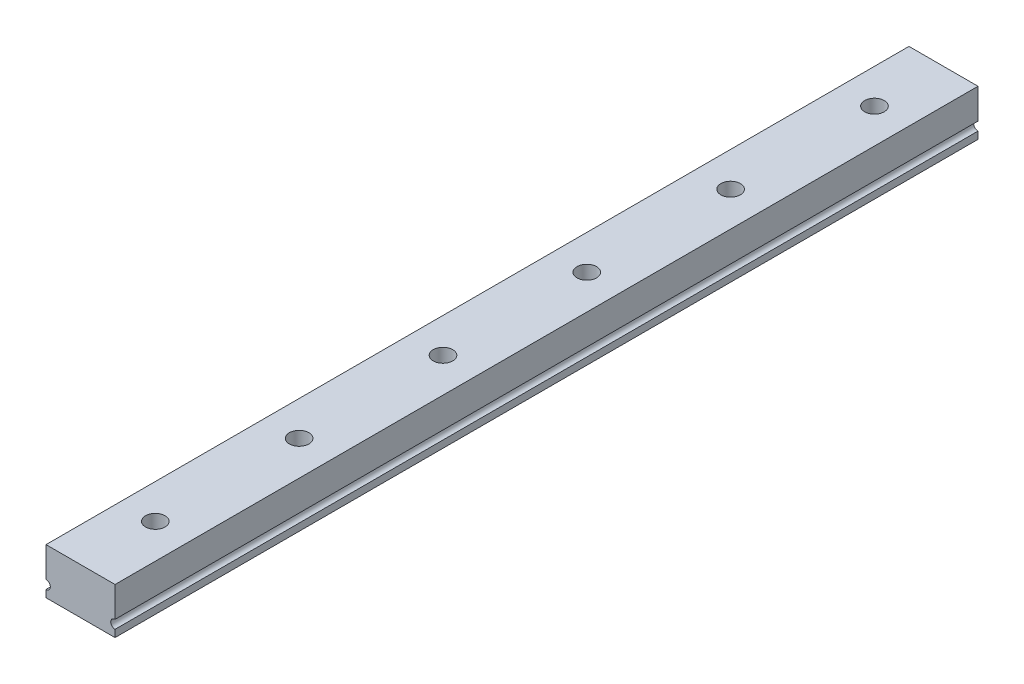
SolidWorks part; units mm, degrees
ref_plane "Front Plane" through (0, 0, 0) normal (0, 0, 1) x (1, 0, 0)
ref_plane "Top Plane" through (0, 0, 0) normal (0, 1, 0) x (1, 0, 0)
ref_plane "Right Plane" through (0, 0, 0) normal (1, 0, 0) x (0, 0, -1)
sketch "Sketch1" plane through (0, 0, 0) normal (0, 0, 1) x (1, 0, 0)
  line L0 (-15, -20) -> (15, -20) construction
  line L1 (-6, -28) -> (6, -28)
  line L2 (-6, -28) -> (-6, -20)
  line L3 (-6, -20) -> (6, -20)
  line L4 (6, -28) -> (6, -20)
  line L5 (-6, -28) -> (6, -20) construction
  line L6 (-6, -20) -> (6, -28) construction
  point P0 (0, -24)
  dimension "D1" = 8
  dimension "D2" = 12
extrude "Boss-Extrude1" add sketch "Sketch1" against normal blind 150 from offset 50 offset against normal yes
sketch "Sketch2" plane through (0, 0, -50) normal (0, 0, 1) x (1, 0, 0)
  line L0 (-6, -20) -> (-6, -28) construction
  line L1 (6, -28) -> (6, -20) construction
  line L2 (-6, -28) -> (6, -28) construction
  circle A0 centre (-6, -26) radius 0.75
  circle A1 centre (6, -26) radius 0.75
  dimension "D2" = 1.5
  dimension "D1" = 2
extrude "Cut-Extrude1" cut sketch "Sketch2" against normal up to next
hole_wizard "CBORE for M3 Hex Head Cap Screw1" positions "Sketch4" profile "Sketch5" counterbore size "M3" standard "ISO" end condition up to next
sketch "Sketch4" plane through (0, -28, 0) normal (0, -1, 0) x (-1, 0, 0)
  line L0 (6, 50) -> (-6, 50) construction
  point P0 (0, 63)
  dimension "D1" = 13
sketch "Sketch5" plane through (0, -28, -63) normal (1, 0, 0) x (0, 0, -1)
  line L0 (0, 0) -> (0, 8)
  line L1 (0, 8) -> (1.7, 8)
  line L3 (1.7, 8) -> (1.7, 2)
  line L4 (1.7, 2) -> (4.6755, 2)
  line L5 (4.6755, 2) -> (4.6755, 0)
  line L7 (4.6755, 0) -> (0, 0)
  line L11 (0, -6.35) -> (0, 107.95) construction
  dimension "Thru Hole Dia." = 3.4
  dimension "Thru Hole Depth" = 8
  dimension "C'Bore Dia." = 9.351
  dimension "C'Bore Depth" = 2
pattern_linear "LPattern2" count 6 spacing 25 along (0, 0, -1) of "CBORE for M3 Hex Head Cap Screw1"
